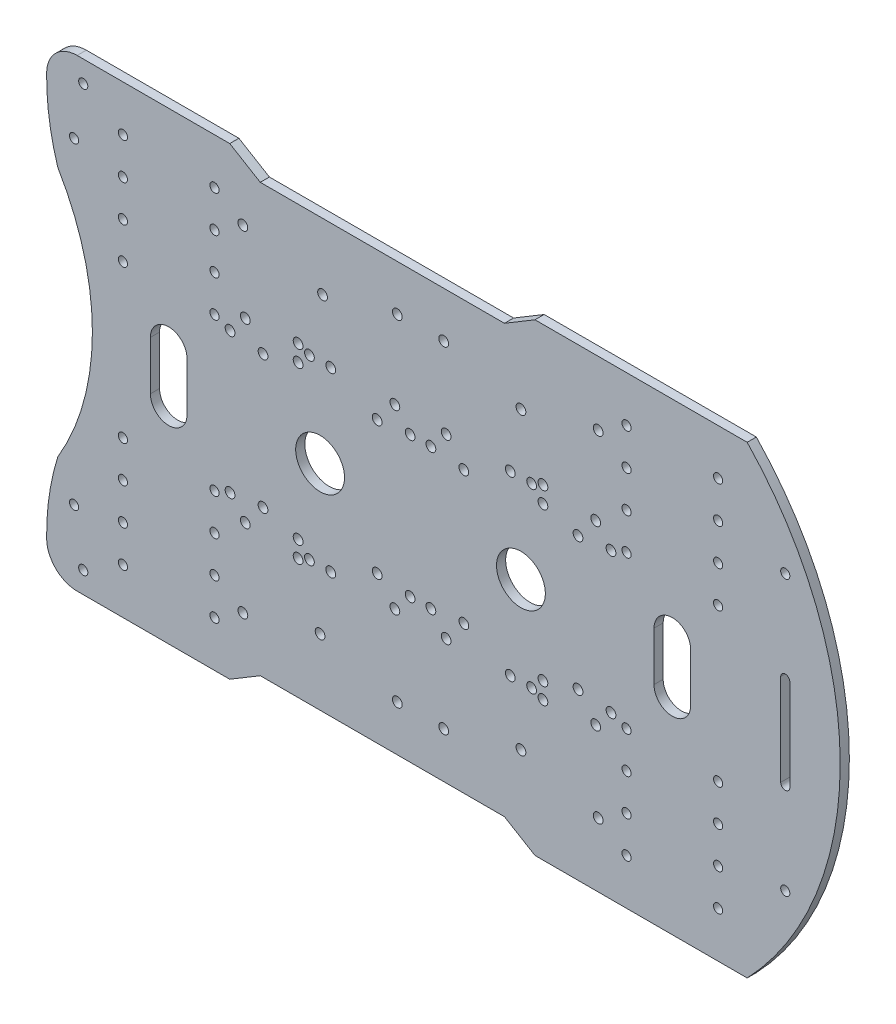
SolidWorks part; units mm, degrees
ref_plane "Front Plane" through (0, 0, 0) normal (0, 0, 1) x (1, 0, 0)
ref_plane "Top Plane" through (0, 0, 0) normal (0, 1, 0) x (1, 0, 0)
ref_plane "Right Plane" through (0, 0, 0) normal (1, 0, 0) x (0, 0, -1)
sketch "Model" plane through (0, 0, 0) normal (0, 0, 1) x (1, 0, 0)
  line L0 (404, 14.25) -> (584, 14.25)
  line L1 (584, 48.25) -> (404, 48.25)
  line L2 (404, 65.25) -> (584, 65.25)
  line L3 (430.991, 48.25) -> (430.991, 10)
  line L4 (502.8, 31.25) -> (404, 31.25)
  line L5 (502.8, 35.5) -> (404, 35.5)
  line L6 (502.8, 39.75) -> (404, 39.75)
  line L7 (502.8, 44) -> (404, 44)
  line L8 (458.6, 10) -> (458.6, 48.25)
  line L9 (404, 65.25) -> (404, 10)
  line L10 (411.8, 48.25) -> (411.8, 10)
  line L11 (437.8, 48.25) -> (437.8, 65.25)
  line L12 (448.3989, 48.25) -> (448.3989, 10)
  line L13 (469, 31.25) -> (469, 48.25)
  line L14 (458.6, 18.5) -> (404, 18.5)
  line L15 (484.6, 65.25) -> (484.6, 27)
  line L16 (458.6, 22.7499) -> (404, 22.7499)
  line L17 (458.6, 27) -> (404, 27)
  line L18 (458.6, 27) -> (584, 27)
  line L19 (502.8, 65.25) -> (502.8, 10)
  line L20 (547, 10) -> (547, 14.25)
  line L21 (554.8, 58.875) -> (554.8, 65.25)
  line L22 (571, 14.25) -> (571, 27)
  line L23 (584, 58.875) -> (502.8, 58.875)
  line L24 (584, 18.5) -> (571, 18.5)
  line L25 (20, 10) -> (20, 410)
  line L26 (20, 410) -> (584, 410)
  line L27 (584, 410) -> (584, 10)
  line L28 (584, 10) -> (20, 10)
  line L29 (15, 5) -> (15, 415)
  line L30 (15, 415) -> (589, 415)
  line L31 (589, 415) -> (589, 5)
  line L32 (589, 5) -> (15, 5)
  line L33 (15, 210) -> (25, 210)
  line L34 (302, 415) -> (302, 405)
  line L35 (589, 210) -> (579, 210)
  line L36 (302, 5) -> (302, 15)
  line L37 (20, 60) -> (15, 60)
  line L38 (584, 60) -> (589, 60)
  line L39 (20, 110) -> (15, 110)
  line L40 (584, 110) -> (589, 110)
  line L41 (20, 160) -> (15, 160)
  line L42 (584, 160) -> (589, 160)
  line L43 (20, 210) -> (15, 210)
  line L44 (584, 210) -> (589, 210)
  line L45 (20, 260) -> (15, 260)
  line L46 (584, 260) -> (589, 260)
  line L47 (20, 310) -> (15, 310)
  line L48 (584, 310) -> (589, 310)
  line L49 (20, 360) -> (15, 360)
  line L50 (584, 360) -> (589, 360)
  line L51 (52, 410) -> (52, 415)
  line L52 (52, 10) -> (52, 5)
  line L53 (102, 410) -> (102, 415)
  line L54 (102, 10) -> (102, 5)
  line L55 (152, 410) -> (152, 415)
  line L56 (152, 10) -> (152, 5)
  line L57 (202, 410) -> (202, 415)
  line L58 (202, 10) -> (202, 5)
  line L59 (252, 410) -> (252, 415)
  line L60 (252, 10) -> (252, 5)
  line L61 (302, 410) -> (302, 415)
  line L62 (302, 10) -> (302, 5)
  line L63 (352, 410) -> (352, 415)
  line L64 (352, 10) -> (352, 5)
  line L65 (402, 410) -> (402, 415)
  line L66 (402, 10) -> (402, 5)
  line L67 (452, 410) -> (452, 415)
  line L68 (452, 10) -> (452, 5)
  line L69 (502, 410) -> (502, 415)
  line L70 (502, 10) -> (502, 5)
  line L71 (552, 410) -> (552, 415)
  line L72 (552, 10) -> (552, 5)
  line L73 (307.6913, 297.7528) -> (307.6913, 281.7528)
  line L74 (319.6913, 297.7528) -> (319.6913, 281.7528)
  line L75 (349.1913, 304.7528) -> (349.1913, 274.7528)
  line L76 (352.1913, 304.7528) -> (352.1913, 274.7528)
  line L77 (142.6913, 297.7528) -> (142.6913, 281.7528)
  line L78 (154.6913, 297.7528) -> (154.6913, 281.7528)
  line L79 (118.6985, 365.7528) -> (168.6913, 365.7528)
  line L80 (168.6913, 365.7528) -> (178.6913, 359.7528)
  line L81 (178.6913, 359.7528) -> (258.6913, 359.7528)
  line L82 (258.6913, 359.7528) -> (268.6913, 365.7528)
  line L83 (268.6913, 365.7528) -> (338.2149, 365.7528)
  line L84 (268.6913, 213.7528) -> (338.2149, 213.7528)
  line L85 (258.6913, 219.7528) -> (268.6913, 213.7528)
  line L86 (178.6913, 219.7528) -> (258.6913, 219.7528)
  line L87 (168.6913, 213.7528) -> (178.6913, 219.7528)
  line L88 (118.6985, 213.7528) -> (168.6913, 213.7528)
  line L89 (473.3173, 213.7528) -> (473.3173, 365.7528)
  line L90 (473.3173, 365.7528) -> (476.3173, 365.7528)
  line L91 (473.3173, 213.7528) -> (476.3173, 213.7528)
  line L92 (476.3173, 365.7528) -> (476.3173, 213.7528)
  circle A0 centre (328.6913, 264.7528) radius 1.5
  circle A1 centre (298.6913, 252.7528) radius 1.5
  circle A2 centre (298.6913, 240.7528) radius 1.5
  circle A3 centre (298.6913, 228.7528) radius 1.5
  arc A4 (319.6913, 297.7528) -> (307.6913, 297.7528) centre (313.6913, 297.7528) ccw
  arc A5 (352.1913, 304.7528) -> (349.1913, 304.7528) centre (350.6913, 304.7528) ccw
  circle A6 centre (163.6913, 264.7528) radius 1.5
  circle A7 centre (163.6913, 252.7528) radius 1.5
  circle A8 centre (163.6913, 240.7528) radius 1.5
  circle A9 centre (163.6913, 228.7528) radius 1.5
  circle A10 centre (120.6913, 220.7528) radius 1.5
  arc A11 (154.6913, 297.7528) -> (142.6913, 297.7528) centre (148.6913, 297.7528) ccw
  circle A12 centre (163.6913, 314.7528) radius 1.5
  circle A13 centre (133.6913, 314.7528) radius 1.5
  circle A14 centre (163.6913, 326.7528) radius 1.5
  circle A15 centre (133.6913, 326.7528) radius 1.5
  circle A16 centre (163.6913, 338.7528) radius 1.5
  circle A17 centre (133.6913, 338.7528) radius 1.5
  circle A18 centre (163.6913, 350.7528) radius 1.5
  circle A19 centre (133.6913, 350.7528) radius 1.5
  circle A20 centre (120.6913, 358.7528) radius 1.5
  circle A21 centre (117.6913, 341.7528) radius 1.5
  circle A22 centre (298.6913, 314.7528) radius 1.5
  circle A23 centre (328.6913, 314.7528) radius 1.5
  circle A24 centre (328.6913, 326.7528) radius 1.5
  circle A25 centre (298.6913, 326.7528) radius 1.5
  circle A26 centre (328.6913, 338.7528) radius 1.5
  circle A27 centre (298.6913, 338.7528) radius 1.5
  circle A28 centre (328.6913, 350.7528) radius 1.5
  circle A29 centre (298.6913, 350.7528) radius 1.5
  circle A30 centre (350.6913, 334.7528) radius 1.5
  arc A31 (112.365, 248.717) -> (112.365, 330.7885) centre (43.6913, 289.7528) ccw
  circle A32 centre (117.6913, 237.7528) radius 1.5
  circle A33 centre (133.6913, 228.7528) radius 1.5
  circle A34 centre (133.6913, 240.7528) radius 1.5
  circle A35 centre (133.6913, 252.7528) radius 1.5
  circle A36 centre (133.6913, 264.7528) radius 1.5
  circle A37 centre (350.6913, 244.7528) radius 1.5
  circle A38 centre (328.6913, 228.7528) radius 1.5
  circle A39 centre (328.6913, 240.7528) radius 1.5
  circle A40 centre (328.6913, 252.7528) radius 1.5
  circle A41 centre (298.6913, 264.7528) radius 1.5
  arc A42 (307.6913, 281.7528) -> (319.6913, 281.7528) centre (313.6913, 281.7528) ccw
  arc A43 (349.1913, 274.7528) -> (352.1913, 274.7528) centre (350.6913, 274.7528) ccw
  arc A44 (142.6913, 281.7528) -> (154.6913, 281.7528) centre (148.6913, 281.7528) ccw
  arc A45 (108.6995, 355.8956) -> (112.365, 330.7885) centre (188.6913, 354.7528) ccw
  arc A46 (338.2149, 213.7528) -> (338.2149, 365.7528) centre (258.6913, 289.7528) ccw
  arc A47 (112.365, 248.717) -> (108.6995, 223.6099) centre (188.6913, 224.7528) ccw
  arc A48 (118.6985, 365.7528) -> (108.6995, 355.8956) centre (118.6985, 355.7528) ccw
  arc A49 (108.6995, 223.6099) -> (118.6985, 213.7528) centre (118.6985, 223.7528) ccw
  circle A50 centre (288.5913, 260.7528) radius 1.6
  circle A51 centre (239.5913, 260.7528) radius 1.6
  circle A52 centre (264.0913, 289.7528) radius 8
  circle A53 centre (245.3913, 267.9528) radius 1.6
  circle A54 centre (293.5913, 266.7528) radius 1.6
  circle A55 centre (234.5913, 266.7528) radius 1.6
  circle A56 centre (282.7913, 267.9528) radius 1.6
  circle A57 centre (260.5913, 260.7528) radius 1.6
  circle A58 centre (267.5913, 260.7528) radius 1.6
  circle A59 centre (289.3913, 344.7528) radius 1.6
  circle A60 centre (238.7913, 234.7528) radius 1.6
  circle A61 centre (289.3913, 234.7528) radius 1.6
  circle A62 centre (288.5913, 318.7528) radius 1.6
  circle A63 centre (239.5913, 318.7528) radius 1.6
  circle A64 centre (245.3913, 311.5528) radius 1.6
  circle A65 centre (293.5913, 312.7528) radius 1.6
  circle A66 centre (234.5913, 312.7528) radius 1.6
  circle A67 centre (282.7913, 311.5528) radius 1.6
  circle A68 centre (260.5913, 318.7528) radius 1.6
  circle A69 centre (267.5913, 318.7528) radius 1.6
  circle A70 centre (264.0913, 338.0528) radius 1.6
  circle A71 centre (264.0913, 241.4528) radius 1.6
  circle A72 centre (191.0913, 264.6528) radius 1.6
  circle A73 centre (191.0913, 259.2528) radius 1.6
  circle A74 centre (191.0913, 314.8528) radius 1.6
  circle A75 centre (191.0913, 320.2528) radius 1.6
  circle A76 centre (271.2913, 314.8528) radius 1.6
  circle A77 centre (271.2913, 320.2528) radius 1.6
  circle A78 centre (271.2913, 264.6528) radius 1.6
  circle A79 centre (271.2913, 259.2528) radius 1.6
  circle A80 centre (222.7913, 260.7528) radius 1.6
  circle A81 centre (173.7913, 260.7528) radius 1.6
  circle A82 centre (198.2913, 289.7528) radius 8
  circle A83 centre (179.5913, 267.9528) radius 1.6
  circle A84 centre (227.7913, 266.7528) radius 1.6
  circle A85 centre (168.7913, 266.7528) radius 1.6
  circle A86 centre (216.9913, 267.9528) radius 1.6
  circle A87 centre (194.7913, 260.7528) radius 1.6
  circle A88 centre (201.7913, 260.7528) radius 1.6
  circle A89 centre (172.9913, 344.7528) radius 1.6
  circle A90 centre (223.5913, 344.7528) radius 1.6
  circle A91 centre (172.9913, 234.7528) radius 1.6
  circle A92 centre (223.5913, 234.7528) radius 1.6
  circle A93 centre (222.7913, 318.7528) radius 1.6
  circle A94 centre (173.7913, 318.7528) radius 1.6
  circle A95 centre (179.5913, 311.5528) radius 1.6
  circle A96 centre (227.7913, 312.7528) radius 1.6
  circle A97 centre (168.7913, 312.7528) radius 1.6
  circle A98 centre (216.9913, 311.5528) radius 1.6
  circle A99 centre (194.7913, 318.7528) radius 1.6
  circle A100 centre (201.7913, 318.7528) radius 1.6
  circle A101 centre (199.1008, 338.0528) radius 1.6
  circle A102 centre (198.2913, 241.4528) radius 1.6
  circle A103 centre (238.7913, 344.7528) radius 1.6
  text T0 "除非另外指定:" font "SWTXT" height 1.5
  text T1 "尺寸使用毫米" font "SWTXT" height 1.5
  text T2 "表面粗糙度:" font "SWTXT" height 1.5
  text T3 "公差:" font "SWTXT" height 1.5
  text T4 "线性:" font "SWTXT" height 1.5
  text T5 "角度:" font "SWTXT" height 1.5
  text T6 "将锐边清除" font "SWTXT" height 1.5
  text T7 "毛刺并折断" font "SWTXT" height 1.5
  text T8 "A" font "SWTXT" height 3.9688
  text T9 "A" font "SWTXT" height 3.9688
  text T10 "B" font "SWTXT" height 3.9688
  text T11 "B" font "SWTXT" height 3.9688
  text T12 "C" font "SWTXT" height 3.9688
  text T13 "C" font "SWTXT" height 3.9688
  text T14 "D" font "SWTXT" height 3.9688
  text T15 "D" font "SWTXT" height 3.9688
  text T16 "E" font "SWTXT" height 3.9688
  text T17 "E" font "SWTXT" height 3.9688
  text T18 "F" font "SWTXT" height 3.9688
  text T19 "F" font "SWTXT" height 3.9688
  text T20 "G" font "SWTXT" height 3.9688
  text T21 "G" font "SWTXT" height 3.9688
  text T22 "H" font "SWTXT" height 3.9688
  text T23 "H" font "SWTXT" height 3.9688
  text T24 "12" font "SWTXT" height 3.9688
  text T25 "12" font "SWTXT" height 3.9688
  text T26 "11" font "SWTXT" height 3.9688
  text T27 "11" font "SWTXT" height 3.9688
  text T28 "10" font "SWTXT" height 3.9688
  text T29 "10" font "SWTXT" height 3.9688
  text T30 "9" font "SWTXT" height 3.9688
  text T31 "9" font "SWTXT" height 3.9688
  text T32 "8" font "SWTXT" height 3.9688
  text T33 "8" font "SWTXT" height 3.9688
  text T34 "7" font "SWTXT" height 3.9688
  text T35 "7" font "SWTXT" height 3.9688
  text T36 "6" font "SWTXT" height 3.9688
  text T37 "6" font "SWTXT" height 3.9688
  text T38 "5" font "SWTXT" height 3.9688
  text T39 "5" font "SWTXT" height 3.9688
  text T40 "4" font "SWTXT" height 3.9688
  text T41 "4" font "SWTXT" height 3.9688
  text T42 "3" font "SWTXT" height 3.9688
  text T43 "3" font "SWTXT" height 3.9688
  text T44 "2" font "SWTXT" height 3.9688
  text T45 "2" font "SWTXT" height 3.9688
  text T46 "1" font "SWTXT" height 3.9688
  text T47 "1" font "SWTXT" height 3.9688
  text T48 "绘制" font "SWTXT" height 1.5
  text T49 "检查" font "SWTXT" height 1.5
  text T50 "批准" font "SWTXT" height 1.5
  text T51 "制造" font "SWTXT" height 1.5
  text T52 "验检" font "SWTXT" height 1.5
  text T53 "表面粗糙度:" font "SWTXT" height 1.5
  text T54 "名称" font "SWTXT" height 1.5
  text T55 "签名" font "SWTXT" height 1.5
  text T56 "日期" font "SWTXT" height 1.5
  text T57 "材料:" font "SWTXT" height 1.5
  text T58 "不调整工程图比例" font "SWTXT" height 1.5
  text T59 "修订" font "SWTXT" height 1.5
  text T60 "标题:" font "SWTXT" height 1.5
  text T61 "工程图号" font "SWTXT" height 1.5
  text T62 "比例:1:1" font "SWTXT" height 1.5
  text T63 "图纸 1 (共1)" font "SWTXT" height 1.5
  text T64 "A2" font "SWTXT" height 2.9104
  text T65 "材质 <未指定>" font "SWTXT" height 2.3812
  text T66 "重量: 0.101" font "SWTXT" height 1.4986
  text T67 "底盘A" font "SWTXT" height 6.35
sketch "Sketch2" plane through (0, 0, 0) normal (0, 0, 1) x (1, 0, 0)
  line L0 (118.6985, 213.7528) -> (168.6913, 213.7528) construction
  line L1 (168.6913, 213.7528) -> (178.6913, 219.7528) construction
  line L2 (178.6913, 219.7528) -> (258.6913, 219.7528) construction
  line L3 (258.6913, 219.7528) -> (268.6913, 213.7528) construction
  line L4 (268.6913, 213.7528) -> (338.2149, 213.7528) construction
  line L5 (268.6913, 365.7528) -> (338.2149, 365.7528) construction
  line L6 (258.6913, 359.7528) -> (268.6913, 365.7528) construction
  line L7 (178.6913, 359.7528) -> (258.6913, 359.7528) construction
  line L8 (168.6913, 365.7528) -> (178.6913, 359.7528) construction
  line L9 (118.6985, 365.7528) -> (168.6913, 365.7528) construction
  line L10 (118.6985, 213.7528) -> (168.6913, 213.7528)
  line L11 (168.6913, 213.7528) -> (178.6913, 219.7528)
  line L12 (178.6913, 219.7528) -> (258.6913, 219.7528)
  line L13 (258.6913, 219.7528) -> (268.6913, 213.7528)
  line L14 (268.6913, 213.7528) -> (338.2149, 213.7528)
  line L15 (268.6913, 365.7528) -> (338.2149, 365.7528)
  line L16 (258.6913, 359.7528) -> (268.6913, 365.7528)
  line L17 (178.6913, 359.7528) -> (258.6913, 359.7528)
  line L18 (168.6913, 365.7528) -> (178.6913, 359.7528)
  line L19 (118.6985, 365.7528) -> (168.6913, 365.7528)
  line L20 (142.6913, 297.7528) -> (142.6913, 281.7528) construction
  line L21 (154.6913, 297.7528) -> (154.6913, 281.7528) construction
  line L22 (142.6913, 297.7528) -> (142.6913, 281.7528)
  line L23 (154.6913, 297.7528) -> (154.6913, 281.7528)
  line L24 (307.6913, 297.7528) -> (307.6913, 281.7528) construction
  line L25 (319.6913, 297.7528) -> (319.6913, 281.7528) construction
  line L26 (307.6913, 297.7528) -> (307.6913, 281.7528)
  line L27 (319.6913, 297.7528) -> (319.6913, 281.7528)
  line L28 (349.1913, 304.7528) -> (349.1913, 274.7528) construction
  line L29 (352.1913, 304.7528) -> (352.1913, 274.7528) construction
  line L30 (349.1913, 304.7528) -> (349.1913, 274.7528)
  line L31 (352.1913, 304.7528) -> (352.1913, 274.7528)
  arc A0 (112.365, 248.717) -> (108.6995, 223.6099) centre (188.6913, 224.7528) ccw construction
  arc A1 (108.6995, 223.6099) -> (118.6985, 213.7528) centre (118.6985, 223.7528) ccw construction
  arc A2 (338.2149, 213.7528) -> (338.2149, 365.7528) centre (258.6913, 289.7528) ccw construction
  arc A3 (118.6985, 365.7528) -> (108.6995, 355.8956) centre (118.6985, 355.7528) ccw construction
  arc A4 (108.6995, 355.8956) -> (112.365, 330.7885) centre (188.6913, 354.7528) ccw construction
  arc A5 (112.365, 248.717) -> (112.365, 330.7885) centre (43.6913, 289.7528) ccw construction
  arc A6 (112.365, 248.717) -> (108.6995, 223.6099) centre (188.6913, 224.7528) ccw
  arc A7 (108.6995, 223.6099) -> (118.6985, 213.7528) centre (118.6985, 223.7528) ccw
  arc A8 (338.2149, 213.7528) -> (338.2149, 365.7528) centre (258.6913, 289.7528) ccw
  arc A9 (118.6985, 365.7528) -> (108.6995, 355.8956) centre (118.6985, 355.7528) ccw
  arc A10 (108.6995, 355.8956) -> (112.365, 330.7885) centre (188.6913, 354.7528) ccw
  arc A11 (112.365, 248.717) -> (112.365, 330.7885) centre (43.6913, 289.7528) ccw
  arc A12 (154.6913, 297.7528) -> (142.6913, 297.7528) centre (148.6913, 297.7528) ccw construction
  arc A13 (142.6913, 281.7528) -> (154.6913, 281.7528) centre (148.6913, 281.7528) ccw construction
  arc A14 (154.6913, 297.7528) -> (142.6913, 297.7528) centre (148.6913, 297.7528) ccw
  arc A15 (142.6913, 281.7528) -> (154.6913, 281.7528) centre (148.6913, 281.7528) ccw
  circle A16 centre (198.2913, 289.7528) radius 8 construction
  circle A17 centre (198.2913, 289.7528) radius 8
  circle A18 centre (264.0913, 289.7528) radius 8 construction
  circle A19 centre (264.0913, 289.7528) radius 8
  arc A20 (319.6913, 297.7528) -> (307.6913, 297.7528) centre (313.6913, 297.7528) ccw construction
  arc A21 (307.6913, 281.7528) -> (319.6913, 281.7528) centre (313.6913, 281.7528) ccw construction
  arc A22 (319.6913, 297.7528) -> (307.6913, 297.7528) centre (313.6913, 297.7528) ccw
  arc A23 (307.6913, 281.7528) -> (319.6913, 281.7528) centre (313.6913, 281.7528) ccw
  arc A24 (352.1913, 304.7528) -> (349.1913, 304.7528) centre (350.6913, 304.7528) ccw construction
  arc A25 (349.1913, 274.7528) -> (352.1913, 274.7528) centre (350.6913, 274.7528) ccw construction
  arc A26 (352.1913, 304.7528) -> (349.1913, 304.7528) centre (350.6913, 304.7528) ccw
  arc A27 (349.1913, 274.7528) -> (352.1913, 274.7528) centre (350.6913, 274.7528) ccw
  circle A28 centre (264.0913, 338.0528) radius 1.6 construction
  circle A29 centre (260.5913, 318.7528) radius 1.6 construction
  circle A30 centre (245.3913, 311.5528) radius 1.6 construction
  circle A31 centre (238.7913, 344.7528) radius 1.6 construction
  circle A32 centre (239.5913, 318.7528) radius 1.6 construction
  circle A33 centre (234.5913, 312.7528) radius 1.6 construction
  circle A34 centre (227.7913, 312.7528) radius 1.6 construction
  circle A35 centre (216.9913, 311.5528) radius 1.6 construction
  circle A36 centre (222.7913, 318.7528) radius 1.6 construction
  circle A37 centre (223.5913, 344.7528) radius 1.6 construction
  circle A38 centre (201.7913, 318.7528) radius 1.6 construction
  circle A39 centre (194.7913, 318.7528) radius 1.6 construction
  circle A40 centre (199.1008, 338.0528) radius 1.6 construction
  circle A41 centre (191.0913, 320.2528) radius 1.6 construction
  circle A42 centre (191.0913, 314.8528) radius 1.6 construction
  circle A43 centre (179.5913, 311.5528) radius 1.6 construction
  circle A44 centre (173.7913, 318.7528) radius 1.6 construction
  circle A45 centre (168.7913, 312.7528) radius 1.6 construction
  circle A46 centre (163.6913, 314.7528) radius 1.5 construction
  circle A47 centre (163.6913, 326.7528) radius 1.5 construction
  circle A48 centre (163.6913, 338.7528) radius 1.5 construction
  circle A49 centre (172.9913, 344.7528) radius 1.6 construction
  circle A50 centre (163.6913, 350.7528) radius 1.5 construction
  circle A51 centre (133.6913, 350.7528) radius 1.5 construction
  circle A52 centre (120.6913, 358.7528) radius 1.5 construction
  circle A53 centre (117.6913, 341.7528) radius 1.5 construction
  circle A54 centre (133.6913, 338.7528) radius 1.5 construction
  circle A55 centre (133.6913, 326.7528) radius 1.5 construction
  circle A56 centre (133.6913, 314.7528) radius 1.5 construction
  circle A57 centre (264.0913, 338.0528) radius 1.6
  circle A58 centre (260.5913, 318.7528) radius 1.6
  circle A59 centre (245.3913, 311.5528) radius 1.6
  circle A60 centre (238.7913, 344.7528) radius 1.6
  circle A61 centre (239.5913, 318.7528) radius 1.6
  circle A62 centre (234.5913, 312.7528) radius 1.6
  circle A63 centre (227.7913, 312.7528) radius 1.6
  circle A64 centre (216.9913, 311.5528) radius 1.6
  circle A65 centre (222.7913, 318.7528) radius 1.6
  circle A66 centre (223.5913, 344.7528) radius 1.6
  circle A67 centre (201.7913, 318.7528) radius 1.6
  circle A68 centre (194.7913, 318.7528) radius 1.6
  circle A69 centre (199.1008, 338.0528) radius 1.6
  circle A70 centre (191.0913, 320.2528) radius 1.6
  circle A71 centre (191.0913, 314.8528) radius 1.6
  circle A72 centre (179.5913, 311.5528) radius 1.6
  circle A73 centre (173.7913, 318.7528) radius 1.6
  circle A74 centre (168.7913, 312.7528) radius 1.6
  circle A75 centre (163.6913, 314.7528) radius 1.5
  circle A76 centre (163.6913, 326.7528) radius 1.5
  circle A77 centre (163.6913, 338.7528) radius 1.5
  circle A78 centre (172.9913, 344.7528) radius 1.6
  circle A79 centre (163.6913, 350.7528) radius 1.5
  circle A80 centre (133.6913, 350.7528) radius 1.5
  circle A81 centre (120.6913, 358.7528) radius 1.5
  circle A82 centre (117.6913, 341.7528) radius 1.5
  circle A83 centre (133.6913, 338.7528) radius 1.5
  circle A84 centre (133.6913, 326.7528) radius 1.5
  circle A85 centre (133.6913, 314.7528) radius 1.5
  circle A86 centre (198.2913, 241.4528) radius 1.6 construction
  circle A87 centre (201.7913, 260.7528) radius 1.6 construction
  circle A88 centre (216.9913, 267.9528) radius 1.6 construction
  circle A89 centre (227.7913, 266.7528) radius 1.6 construction
  circle A90 centre (222.7913, 260.7528) radius 1.6 construction
  circle A91 centre (223.5913, 234.7528) radius 1.6 construction
  circle A92 centre (238.7913, 234.7528) radius 1.6 construction
  circle A93 centre (234.5913, 266.7528) radius 1.6 construction
  circle A94 centre (245.3913, 267.9528) radius 1.6 construction
  circle A95 centre (239.5913, 260.7528) radius 1.6 construction
  circle A96 centre (264.0913, 241.4528) radius 1.6 construction
  circle A97 centre (260.5913, 260.7528) radius 1.6 construction
  circle A98 centre (267.5913, 260.7528) radius 1.6 construction
  circle A99 centre (271.2913, 264.6528) radius 1.6 construction
  circle A100 centre (271.2913, 259.2528) radius 1.6 construction
  circle A101 centre (289.3913, 234.7528) radius 1.6 construction
  circle A102 centre (298.6913, 228.7528) radius 1.5 construction
  circle A103 centre (298.6913, 240.7528) radius 1.5 construction
  circle A104 centre (288.5913, 260.7528) radius 1.6 construction
  circle A105 centre (282.7913, 267.9528) radius 1.6 construction
  circle A106 centre (293.5913, 266.7528) radius 1.6 construction
  circle A107 centre (298.6913, 264.7528) radius 1.5 construction
  circle A108 centre (298.6913, 252.7528) radius 1.5 construction
  circle A109 centre (328.6913, 228.7528) radius 1.5 construction
  circle A110 centre (328.6913, 240.7528) radius 1.5 construction
  circle A111 centre (328.6913, 252.7528) radius 1.5 construction
  circle A112 centre (328.6913, 264.7528) radius 1.5 construction
  circle A113 centre (350.6913, 244.7528) radius 1.5 construction
  circle A114 centre (350.6913, 334.7528) radius 1.5 construction
  circle A115 centre (328.6913, 350.7528) radius 1.5 construction
  circle A116 centre (328.6913, 338.7528) radius 1.5 construction
  circle A117 centre (328.6913, 326.7528) radius 1.5 construction
  circle A118 centre (328.6913, 314.7528) radius 1.5 construction
  circle A119 centre (282.7913, 311.5528) radius 1.6 construction
  circle A120 centre (288.5913, 318.7528) radius 1.6 construction
  circle A121 centre (293.5913, 312.7528) radius 1.6 construction
  circle A122 centre (298.6913, 314.7528) radius 1.5 construction
  circle A123 centre (298.6913, 326.7528) radius 1.5 construction
  circle A124 centre (298.6913, 338.7528) radius 1.5 construction
  circle A125 centre (298.6913, 350.7528) radius 1.5 construction
  circle A126 centre (289.3913, 344.7528) radius 1.6 construction
  circle A127 centre (271.2913, 320.2528) radius 1.6 construction
  circle A128 centre (271.2913, 314.8528) radius 1.6 construction
  circle A129 centre (267.5913, 318.7528) radius 1.6 construction
  circle A130 centre (198.2913, 241.4528) radius 1.6
  circle A131 centre (201.7913, 260.7528) radius 1.6
  circle A132 centre (216.9913, 267.9528) radius 1.6
  circle A133 centre (227.7913, 266.7528) radius 1.6
  circle A134 centre (222.7913, 260.7528) radius 1.6
  circle A135 centre (223.5913, 234.7528) radius 1.6
  circle A136 centre (238.7913, 234.7528) radius 1.6
  circle A137 centre (234.5913, 266.7528) radius 1.6
  circle A138 centre (245.3913, 267.9528) radius 1.6
  circle A139 centre (239.5913, 260.7528) radius 1.6
  circle A140 centre (264.0913, 241.4528) radius 1.6
  circle A141 centre (260.5913, 260.7528) radius 1.6
  circle A142 centre (267.5913, 260.7528) radius 1.6
  circle A143 centre (271.2913, 264.6528) radius 1.6
  circle A144 centre (271.2913, 259.2528) radius 1.6
  circle A145 centre (289.3913, 234.7528) radius 1.6
  circle A146 centre (298.6913, 228.7528) radius 1.5
  circle A147 centre (298.6913, 240.7528) radius 1.5
  circle A148 centre (288.5913, 260.7528) radius 1.6
  circle A149 centre (282.7913, 267.9528) radius 1.6
  circle A150 centre (293.5913, 266.7528) radius 1.6
  circle A151 centre (298.6913, 264.7528) radius 1.5
  circle A152 centre (298.6913, 252.7528) radius 1.5
  circle A153 centre (328.6913, 228.7528) radius 1.5
  circle A154 centre (328.6913, 240.7528) radius 1.5
  circle A155 centre (328.6913, 252.7528) radius 1.5
  circle A156 centre (328.6913, 264.7528) radius 1.5
  circle A157 centre (350.6913, 244.7528) radius 1.5
  circle A158 centre (350.6913, 334.7528) radius 1.5
  circle A159 centre (328.6913, 350.7528) radius 1.5
  circle A160 centre (328.6913, 338.7528) radius 1.5
  circle A161 centre (328.6913, 326.7528) radius 1.5
  circle A162 centre (328.6913, 314.7528) radius 1.5
  circle A163 centre (282.7913, 311.5528) radius 1.6
  circle A164 centre (288.5913, 318.7528) radius 1.6
  circle A165 centre (293.5913, 312.7528) radius 1.6
  circle A166 centre (298.6913, 314.7528) radius 1.5
  circle A167 centre (298.6913, 326.7528) radius 1.5
  circle A168 centre (298.6913, 338.7528) radius 1.5
  circle A169 centre (298.6913, 350.7528) radius 1.5
  circle A170 centre (289.3913, 344.7528) radius 1.6
  circle A171 centre (271.2913, 320.2528) radius 1.6
  circle A172 centre (271.2913, 314.8528) radius 1.6
  circle A173 centre (267.5913, 318.7528) radius 1.6
  circle A174 centre (120.6913, 220.7528) radius 1.5 construction
  circle A175 centre (117.6913, 237.7528) radius 1.5 construction
  circle A176 centre (133.6913, 264.7528) radius 1.5 construction
  circle A177 centre (133.6913, 252.7528) radius 1.5 construction
  circle A178 centre (133.6913, 240.7528) radius 1.5 construction
  circle A179 centre (133.6913, 228.7528) radius 1.5 construction
  circle A180 centre (163.6913, 228.7528) radius 1.5 construction
  circle A181 centre (163.6913, 240.7528) radius 1.5 construction
  circle A182 centre (172.9913, 234.7528) radius 1.6 construction
  circle A183 centre (163.6913, 252.7528) radius 1.5 construction
  circle A184 centre (163.6913, 264.7528) radius 1.5 construction
  circle A185 centre (168.7913, 266.7528) radius 1.6 construction
  circle A186 centre (173.7913, 260.7528) radius 1.6 construction
  circle A187 centre (179.5913, 267.9528) radius 1.6 construction
  circle A188 centre (191.0913, 264.6528) radius 1.6 construction
  circle A189 centre (194.7913, 260.7528) radius 1.6 construction
  circle A190 centre (191.0913, 259.2528) radius 1.6 construction
  circle A191 centre (120.6913, 220.7528) radius 1.5
  circle A192 centre (117.6913, 237.7528) radius 1.5
  circle A193 centre (133.6913, 264.7528) radius 1.5
  circle A194 centre (133.6913, 252.7528) radius 1.5
  circle A195 centre (133.6913, 240.7528) radius 1.5
  circle A196 centre (133.6913, 228.7528) radius 1.5
  circle A197 centre (163.6913, 228.7528) radius 1.5
  circle A198 centre (163.6913, 240.7528) radius 1.5
  circle A199 centre (172.9913, 234.7528) radius 1.6
  circle A200 centre (163.6913, 252.7528) radius 1.5
  circle A201 centre (163.6913, 264.7528) radius 1.5
  circle A202 centre (168.7913, 266.7528) radius 1.6
  circle A203 centre (173.7913, 260.7528) radius 1.6
  circle A204 centre (179.5913, 267.9528) radius 1.6
  circle A205 centre (191.0913, 264.6528) radius 1.6
  circle A206 centre (194.7913, 260.7528) radius 1.6
  circle A207 centre (191.0913, 259.2528) radius 1.6
extrude "Boss-Extrude1" add sketch "Sketch2" along normal blind 3
ref_plane "Plane1" through (0, 289.7528, 0) normal (0, -1, 0) x (-1, 0, 0)
